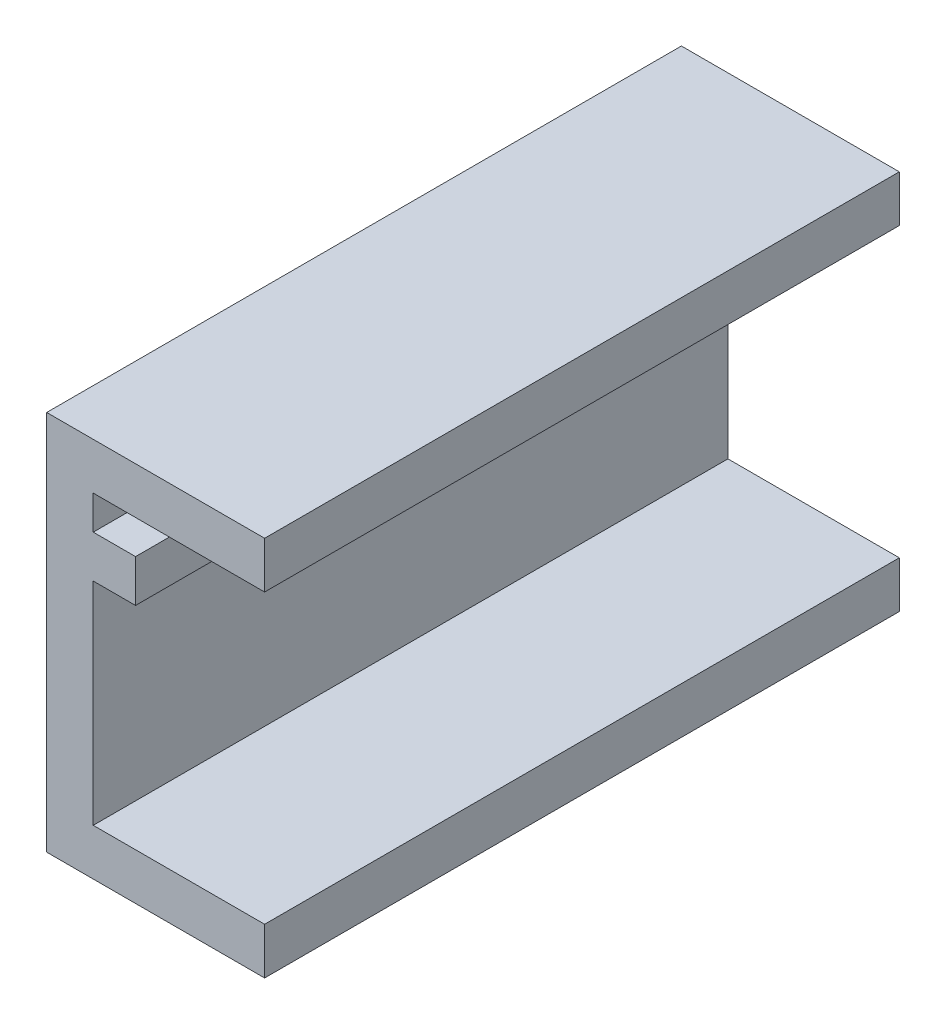
SolidWorks part; units mm, degrees
ref_plane "Front Plane" through (0, 0, 0) normal (0, 0, 1) x (1, 0, 0)
ref_plane "Top Plane" through (0, 0, 0) normal (0, 1, 0) x (1, 0, 0)
ref_plane "Right Plane" through (0, 0, 0) normal (1, 0, 0) x (0, 0, -1)
sketch "Sketch1" plane through (0, 0, 0) normal (0, 0, 1) x (1, 0, 0)
  line L0 (-8.1, 14.2) -> (-6.1, 14.2)
  line L1 (0, -15.9149) -> (0, 15.9149) construction
  line L2 (-8.1, 14.2) -> (-8.1, 15.8)
  line L3 (-8.1, 15.8) -> (0, 15.8)
  line L4 (0, 15.8) -> (0, 18)
  line L5 (0, 18) -> (-10.3, 18)
  line L6 (-6.1, 14.2) -> (-6.1, 12.2)
  line L7 (-6.1, 12.2) -> (-8.1, 12.2)
  line L8 (-8.1, 12.2) -> (-8.1, 2.2)
  line L9 (-8.1, 2.2) -> (0, 2.2)
  line L10 (0, 2.2) -> (0, 0)
  line L11 (-10.3, 18) -> (-10.3, 0)
  line L12 (-10.3, 0) -> (0, 0)
  dimension "D1" = 1.6
  dimension "D2" = 2
  dimension "D3" = 2.2
  dimension "D4" = 2.2
  dimension "D5" = 2.2
  dimension "D6" = 2
  dimension "D7" = 10
  dimension "D8" = 8.1
extrude "Boss-Extrude1" add sketch "Sketch1" along normal blind 30
